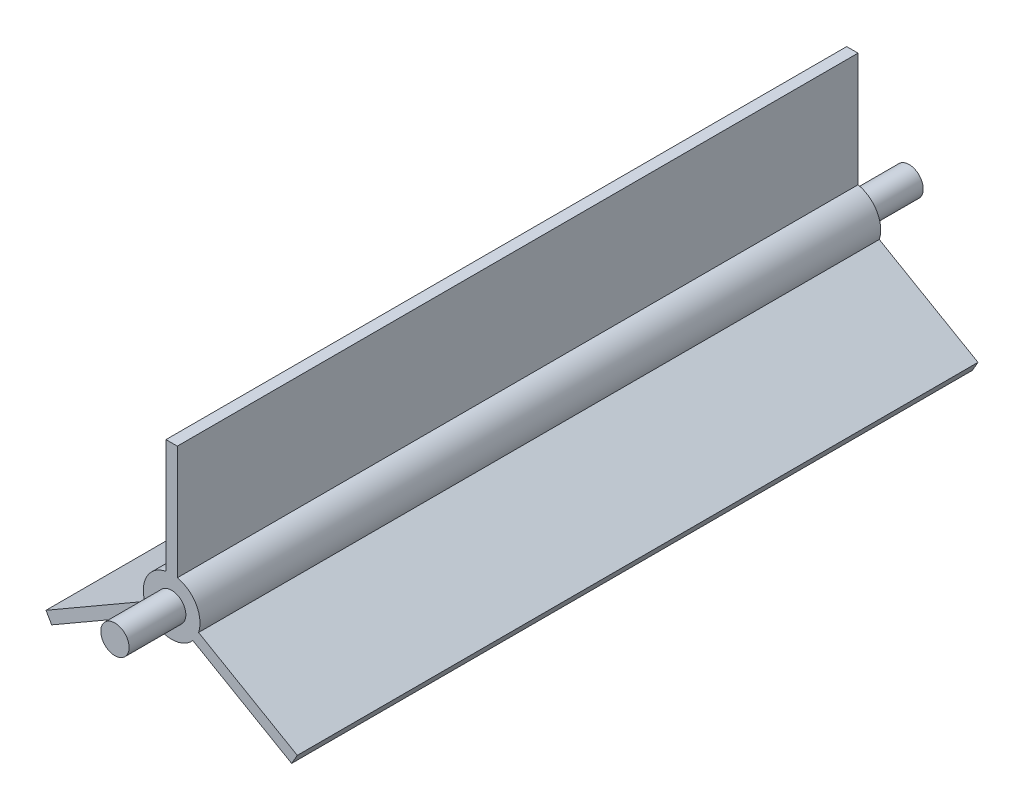
SolidWorks part; units mm, degrees
ref_plane "Front Plane" through (0, 0, 0) normal (0, 0, 1) x (1, 0, 0)
ref_plane "Top Plane" through (0, 0, 0) normal (0, 1, 0) x (1, 0, 0)
ref_plane "Right Plane" through (0, 0, 0) normal (1, 0, 0) x (0, 0, -1)
sketch "Sketch1" plane through (0, 0, 0) normal (0, 0, 1) x (1, 0, 0)
  line L0 (0, 0) -> (0, 63.5)
  line L1 (0, 0) -> (54.9926, -31.75)
  line L2 (54.9926, -31.75) -> (0, 0)
  line L3 (0, 0) -> (-54.9926, -31.75)
  line L4 (2.54, 1.4665) -> (2.54, 63.5)
  line L5 (-2.54, 1.4665) -> (-56.2626, -29.5503)
  line L6 (-2.54, 1.4665) -> (-2.54, 63.5)
  line L7 (0, -2.9329) -> (-53.7226, -33.9497)
  line L8 (0, -2.9329) -> (53.7226, -33.9497)
  line L9 (2.54, 1.4665) -> (56.2626, -29.5503)
  line L10 (1.27, -2.1997) -> (-53.7226, -33.9497) construction
  line L11 (-1.27, -2.1997) -> (53.7226, -33.9497) construction
  line L12 (-1.27, 2.1997) -> (-56.2626, -29.5503) construction
  line L13 (-2.54, 0) -> (-2.54, 63.5) construction
  line L14 (1.27, 2.1997) -> (56.2626, -29.5503) construction
  line L15 (2.54, 0) -> (2.54, 63.5) construction
  line L16 (56.2626, -29.5503) -> (53.7226, -33.9497)
  line L17 (-56.2626, -29.5503) -> (-53.7226, -33.9497)
  line L18 (-2.54, 63.5) -> (2.54, 63.5)
  circle A0 centre (0, 0) radius 63.5 construction
  circle A1 centre (0, 0) radius 12.7
  dimension "D1" = 120
  dimension "D3" = 127
  dimension "D4" = 25.4
  dimension "D2" = 120
  dimension "D5" = 2.54
  dimension "D6" = 2.54
  dimension "D7" = 2.54
  dimension "D8" = 2.54
extrude "Boss-Extrude1" add sketch "Sketch1" along normal blind 304.8 contours L6 A1 L5 | L7 A1 L8 | L9 A1 L4 | L3 A1 L7 L8 L1 | L0 A1 L6 L5 L3 | L4 A1 L0 L1 L9 | A1 L4 L18 L0 | A1 L0 L18 L6 | A1 L5 L17 L3 | A1 L3 L17 L7 | A1 L8 L16 L2 | A1 L2 L16 L9
sketch "Sketch2" plane through (0, 0, 304.8) normal (0, 0, 1) x (1, 0, 0)
  circle A0 centre (0, 0) radius 6.35
  dimension "D1" = 12.7
extrude "Boss-Extrude2" add sketch "Sketch2" along normal blind 25.4 and the other way blind 330.2
